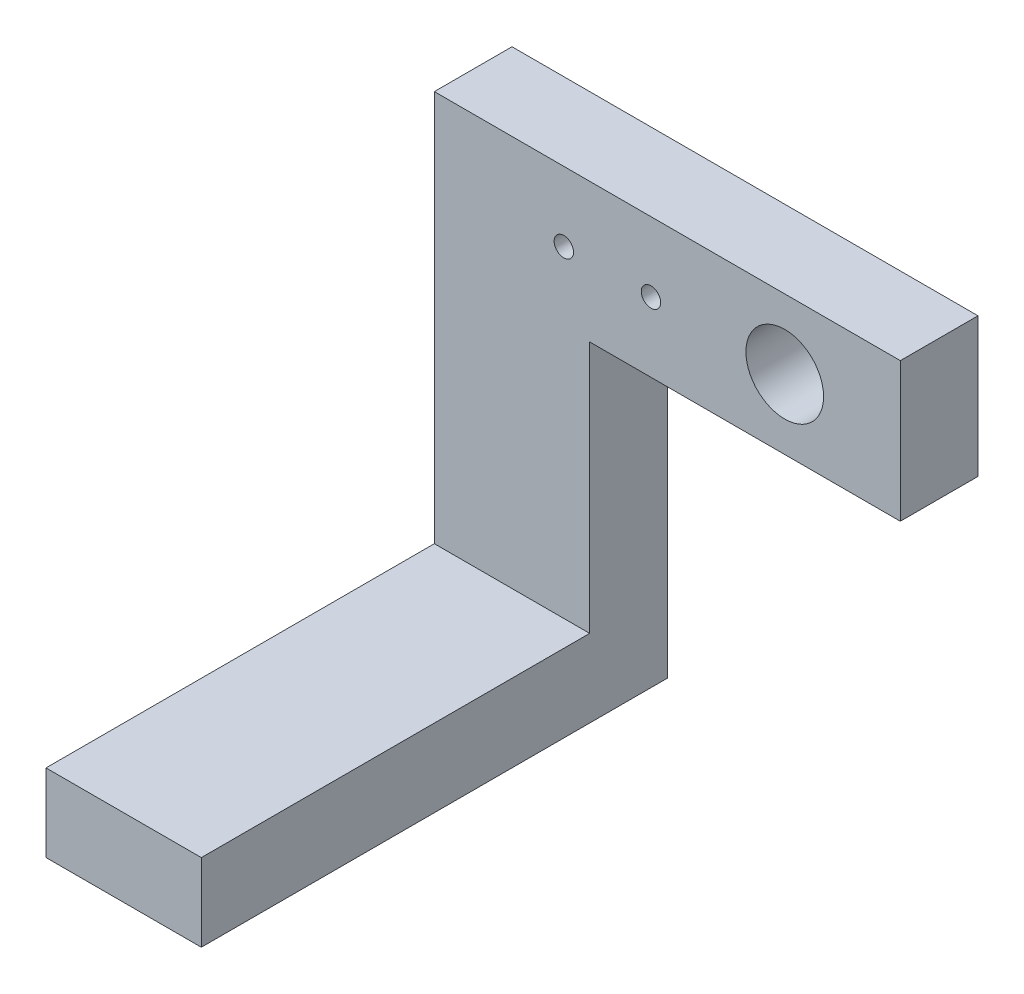
SolidWorks part; units mm, degrees
ref_plane "Front Plane" through (0, 0, 0) normal (0, 0, 1) x (1, 0, 0)
ref_plane "Top Plane" through (0, 0, 0) normal (0, 1, 0) x (1, 0, 0)
ref_plane "Right Plane" through (0, 0, 0) normal (1, 0, 0) x (0, 0, -1)
sketch "Sketch1" plane through (0, 0, 0) normal (0, 0, 1) x (1, 0, 0)
  line L0 (-22.92, -4.55) -> (-22.92, -26.14)
  line L2 (7.56, -4.55) -> (7.56, 4.55)
  line L3 (7.56, 4.55) -> (-22.92, 4.55)
  line L4 (-22.92, -4.55) -> (-22.92, 4.55)
  line L5 (-22.92, -26.14) -> (-12.76, -26.14)
  line L6 (-12.76, -26.14) -> (-12.76, -4.55)
  line L7 (-12.76, -4.55) -> (7.56, -4.55)
  arc A1 (1.9, 6.45) -> (-1.9, 6.45) centre (0, 6.45) ccw construction
  dimension "D1" = 22.92
  dimension "D2" = 30.48
  dimension "D3" = 21.59
  dimension "D4" = 10.16
extrude "Boss-Extrude1" add sketch "Sketch1" along normal blind 5.08 contours L3 L4 L0 L5 L6 L7 L2
sketch "Sketch2" plane through (0, 0, 0) normal (0, 0, -1) x (-1, 0, 0)
  circle A0 centre (14.45, 0) radius 0.635
  circle A2 centre (0, 0) radius 2.54
  circle A3 centre (8.75, 0) radius 0.635
  dimension "D1" = 5.08
  dimension "D2" = 1.27
sketch "Sketch4" plane through (0, 0, 5.08) normal (0, 0, 1) x (1, 0, 0)
  line L0 (-12.76, -26.14) -> (-12.76, -4.55) construction
  line L1 (-22.92, -26.14) -> (-12.76, -26.14)
  line L2 (-22.92, -26.14) -> (-22.92, -21.06)
  line L3 (-22.92, -21.06) -> (-12.76, -21.06)
  line L4 (-12.76, -26.14) -> (-12.76, -21.06)
  dimension "D1" = 5.08
extrude "Boss-Extrude2" add sketch "Sketch4" along normal blind 25.4
extrude "Cut-Extrude1" cut sketch "Sketch2" against normal up to surface (5.08 mm away) up to face at (-9.3733, -7.02, 5.08)
